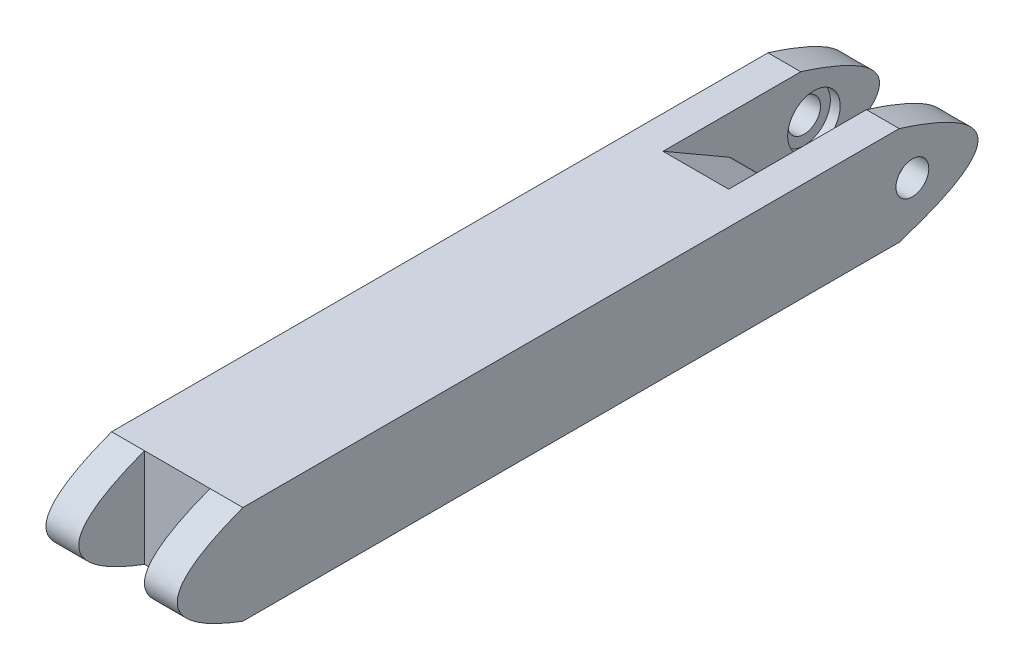
SolidWorks part; units mm, degrees
ref_plane "Front Plane" through (0, 0, 0) normal (0, 0, 1) x (1, 0, 0)
ref_plane "Top Plane" through (0, 0, 0) normal (0, 1, 0) x (1, 0, 0)
ref_plane "Right Plane" through (0, 0, 0) normal (1, 0, 0) x (0, 0, -1)
sketch "Sketch1" plane through (0, 0, 0) normal (1, 0, 0) x (0, 0, -1)
  line L0 (-41.5917, 42.046) -> (58.4083, 42.046)
  line L3 (-41.5917, 27.046) -> (58.4083, 27.046)
  circle A1 centre (60.4083, 34.546) radius 4
  spline S0 degree 2 poles (58.4083, 42.046) (82.4083, 34.546) (58.4083, 27.046) knots 0 0 0 1 1 1
  spline S1 degree 2 poles (-41.5917, 42.046) (-61.5917, 34.546) (-41.5917, 27.046) knots 0 0 0 1 1 1
  dimension "D6" = 10
  dimension "D9" = 10
  dimension "D10" = 8
  dimension "D1" = 100
  dimension "D2" = 15
  dimension "D3" = 7.5
  dimension "D4" = 12
extrude "Boss-Extrude1" add sketch "Sketch1" along normal blind 20
sketch "Sketch2" plane through (0, 0, 0) normal (0, 1, 0) x (1, 0, 0)
  line L0 (20, 70.4083) -> (0, 70.4083) construction
  line L1 (5, 70.4083) -> (15, 70.4083)
  line L2 (5, 70.4083) -> (5, 50.4083)
  line L3 (5, 50.4083) -> (15, 50.4083)
  line L4 (15, 70.4083) -> (15, 50.4083)
  line L6 (0, 70.4083) -> (0, 58.4083) construction
  dimension "D1" = 5
  dimension "D2" = 5
  dimension "D3" = 20
extrude "Cut-Extrude1" cut sketch "Sketch2" along normal blind 52 and the other way blind 35
sketch "Sketch3" plane through (0, 27.046, 0) normal (0, -1, 0) x (1, 0, 0)
  line L0 (20, 51.5917) -> (0, 51.5917) construction
  line L1 (5, 51.5917) -> (15, 51.5917)
  line L2 (5, 51.5917) -> (5, 41.5917)
  line L3 (5, 41.5917) -> (15, 41.5917)
  line L4 (15, 51.5917) -> (15, 41.5917)
  line L5 (20, 41.5917) -> (0, 41.5917) construction
  dimension "D1" = 5
  dimension "D2" = 5
extrude "Cut-Extrude2" cut sketch "Sketch3" against normal blind 52
sketch "Sketch4" plane through (0, 0, 0) normal (-1, 0, 0) x (0, 0, 1)
  line L1 (-58.4083, 42.046) -> (41.5917, 42.046) construction
  line L5 (-50.4083, 34.546) -> (-50.4083, 42.046)
  line L6 (-50.4083, 42.046) -> (-37.418, 42.046)
  line L7 (-50.4083, 34.546) -> (-37.418, 42.046)
  line L8 (-50.4083, 27.046) -> (-50.4083, 42.046) construction
  dimension "D1" = 7.5
  dimension "D2" = 60
  dimension "D3" = 0
extrude "Cut-Extrude3" cut sketch "Sketch4" against normal blind 10 from offset 5 offset against normal yes
sketch "Sketch5" plane through (0, 0, 0) normal (-1, 0, 0) x (0, 0, 1)
  line L0 (-50.4083, 27.046) -> (-50.4083, 34.546)
  line L1 (-50.4083, 34.546) -> (-37.418, 27.046)
  line L2 (41.5917, 27.046) -> (-58.4083, 27.046) construction
  line L3 (-37.418, 27.046) -> (-50.4083, 27.046)
  line L5 (-50.4083, 27.046) -> (-50.4083, 34.546) construction
  dimension "D1" = 7.5
  dimension "D2" = 60
  dimension "D3" = 0
extrude "Cut-Extrude4" cut sketch "Sketch5" against normal blind 10 from offset 5 offset against normal yes
sketch "Sketch6" [suppressed] plane through (0, 42.046, 0) normal (0, 1, 0) x (1, 0, 0)
  line L0 (20, 25.4083) -> (35, 25.4083)
  line L1 (20, 58.4083) -> (20, -41.5917) construction
  line L2 (35, 25.4083) -> (35, 70.4083)
  line L3 (35, 70.4083) -> (30, 70.4083)
  line L4 (30, 70.4083) -> (30, 30.4083)
  line L5 (30, 30.4083) -> (20, 30.4083)
  line L7 (20, 30.4083) -> (20, 25.4083)
  line L9 (20, 70.4083) -> (15, 70.4083) construction
  dimension "D1" = 10
  dimension "D2" = 5
  dimension "D3" = 40
  dimension "D4" = 5
sketch "Sketch7" [suppressed] plane through (35, 0, 0) normal (1, 0, 0) x (0, 0, -1)
  line L1 (25.4083, 42.046) -> (70.4083, 42.046) construction
  line L2 (25.4083, 27.046) -> (25.4083, 42.046) construction
  circle A0 centre (75.4083, 17.046) radius 15
  dimension "D1" = 30
  dimension "D2" = 25
  dimension "D3" = 50
sketch "Sketch8" [suppressed] plane through (35, 0, 0) normal (1, 0, 0) x (0, 0, -1)
  circle A0 centre (75.4083, 29.546) radius 2
  circle A1 centre (75.4083, 17.046) radius 15 construction
  circle A2 centre (87.9083, 17.046) radius 2
  circle A3 centre (75.4083, 4.546) radius 2
  circle A4 centre (62.9083, 17.046) radius 2
  dimension "D2" = 4
  dimension "D1" = 12.5
  dimension "D3" = 12.5
  dimension "D4" = 12.5
  dimension "D5" = 12.5
extrude "Cut-Extrude5" [suppressed] cut sketch "Sketch8" against normal blind 10
fillet "Fillet1" radius 2 1 edges at (10, 34.546, -50.4083)
sketch "Sketch9" plane through (0, 0, 0) normal (-1, 0, 0) x (0, 0, 1)
  circle A0 centre (-60.4083, 34.546) radius 4
  circle A1 centre (-60.4083, 34.546) radius 2.5
  dimension "D1" = 5
extrude "Boss-Extrude2" add sketch "Sketch9" against normal blind 3.5
sketch "Sketch10" plane through (20, 0, 0) normal (1, 0, 0) x (0, 0, -1)
  circle A0 centre (60.4083, 34.546) radius 4
  circle A1 centre (60.4083, 34.546) radius 2.5
  point P4 (60.4083, 34.546)
  dimension "D1" = 5
extrude "Boss-Extrude3" add sketch "Sketch10" against normal blind 3.5
